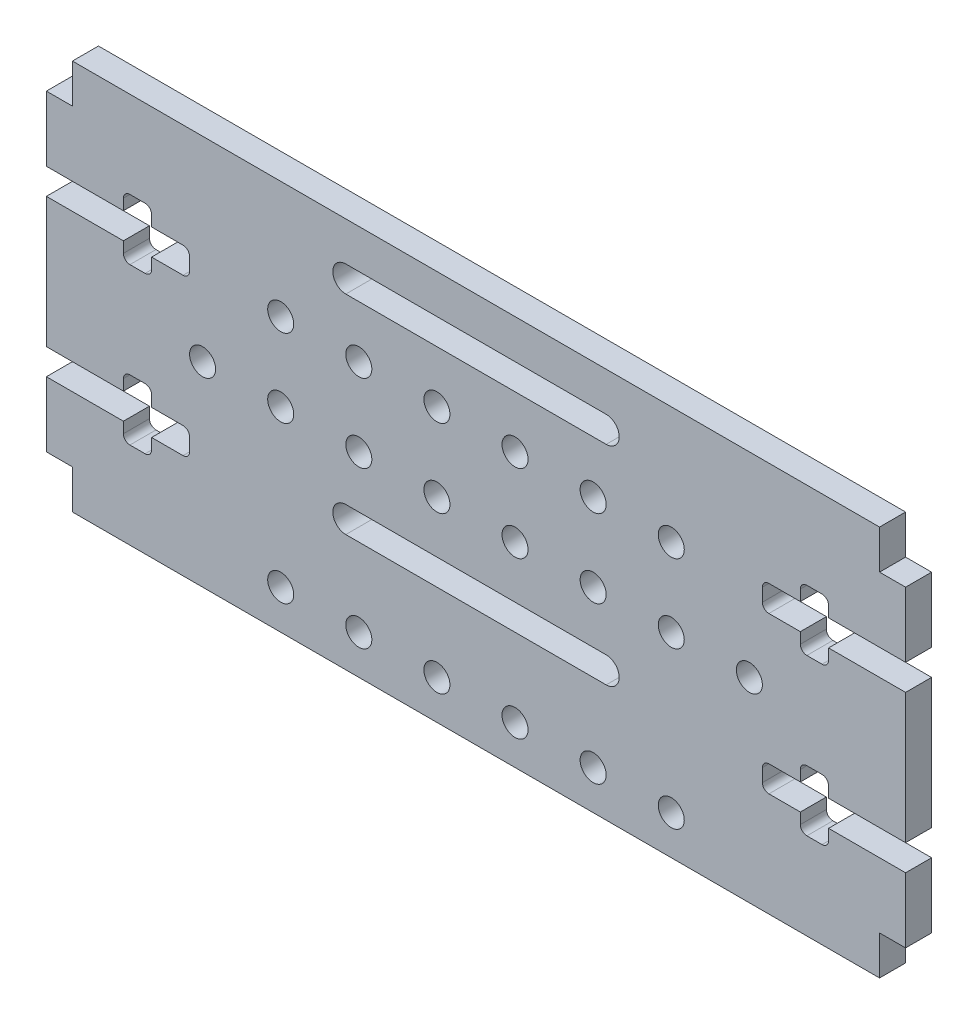
SolidWorks part; units mm, degrees
ref_plane "Alzado" through (0, 0, 0) normal (0, 0, 1) x (1, 0, 0)
ref_plane "Planta" through (0, 0, 0) normal (0, 1, 0) x (1, 0, 0)
ref_plane "Vista lateral" through (0, 0, 0) normal (1, 0, 0) x (0, 0, -1)
sketch "Model" plane through (0, 0, 0) normal (0, 0, 1) x (1, 0, 0)
  line L0 (-1383.7269, 374.4082) -> (-1386.7269, 374.4082)
  line L1 (-1383.7269, 338.4082) -> (-1386.7269, 338.4082)
  line L2 (-1386.7269, 378.9082) -> (-1479.7269, 378.9082)
  line L3 (-1479.7269, 333.9082) -> (-1386.7269, 333.9082)
  line L4 (-1479.7269, 374.4082) -> (-1482.7269, 374.4082)
  line L5 (-1479.7269, 338.4082) -> (-1482.7269, 338.4082)
  line L6 (-1383.7269, 348.9082) -> (-1383.7269, 363.9082)
  line L7 (-1482.7269, 348.9082) -> (-1482.7269, 363.9082)
  line L8 (-1482.7269, 366.9082) -> (-1482.7269, 374.4082)
  line L9 (-1482.7269, 338.4082) -> (-1482.7269, 345.9082)
  line L10 (-1383.7269, 338.4082) -> (-1383.7269, 345.9082)
  line L11 (-1383.7269, 366.9082) -> (-1383.7269, 374.4082)
  line L12 (-1448.2269, 350.4082) -> (-1418.2269, 350.4082)
  line L13 (-1448.2269, 347.4082) -> (-1418.2269, 347.4082)
  line L14 (-1448.2269, 374.4082) -> (-1418.2269, 374.4082)
  line L15 (-1448.2269, 371.4082) -> (-1418.2269, 371.4082)
  line L16 (-1479.7269, 374.4082) -> (-1479.7269, 378.9082)
  line L17 (-1386.7269, 378.9082) -> (-1386.7269, 374.4082)
  line L18 (-1386.7269, 338.4082) -> (-1386.7269, 333.9082)
  line L19 (-1479.7269, 333.9082) -> (-1479.7269, 338.4082)
  line L20 (-1383.7269, 345.9082) -> (-1392.6019, 345.9082)
  line L21 (-1392.6019, 348.9082) -> (-1383.7269, 348.9082)
  line L22 (-1399.4769, 348.9082) -> (-1395.8519, 348.9082)
  line L23 (-1395.8519, 345.9082) -> (-1399.4769, 345.9082)
  line L24 (-1400.2269, 346.6582) -> (-1400.2269, 348.1582)
  line L25 (-1473.8519, 345.9082) -> (-1482.7269, 345.9082)
  line L26 (-1482.7269, 348.9082) -> (-1473.8519, 348.9082)
  line L27 (-1466.9769, 345.9082) -> (-1470.6019, 345.9082)
  line L28 (-1470.6019, 348.9082) -> (-1466.9769, 348.9082)
  line L29 (-1466.2269, 348.1582) -> (-1466.2269, 346.6582)
  line L30 (-1473.1019, 350.9082) -> (-1471.3519, 350.9082)
  line L31 (-1471.3519, 343.9082) -> (-1473.1019, 343.9082)
  line L32 (-1473.8519, 348.9082) -> (-1473.8519, 350.1582)
  line L33 (-1470.6019, 348.9082) -> (-1470.6019, 350.1582)
  line L34 (-1473.8519, 345.9082) -> (-1473.8519, 344.6582)
  line L35 (-1470.6019, 345.9082) -> (-1470.6019, 344.6582)
  line L36 (-1395.1019, 350.9082) -> (-1393.3519, 350.9082)
  line L37 (-1393.3519, 343.9082) -> (-1395.1019, 343.9082)
  line L38 (-1395.8519, 348.9082) -> (-1395.8519, 350.1582)
  line L39 (-1392.6019, 348.9082) -> (-1392.6019, 350.1582)
  line L40 (-1395.8519, 345.9082) -> (-1395.8519, 344.6582)
  line L41 (-1392.6019, 345.9082) -> (-1392.6019, 344.6582)
  line L42 (-1473.8519, 363.9082) -> (-1482.7269, 363.9082)
  line L43 (-1482.7269, 366.9082) -> (-1473.8519, 366.9082)
  line L44 (-1466.9769, 363.9082) -> (-1470.6019, 363.9082)
  line L45 (-1470.6019, 366.9082) -> (-1466.9769, 366.9082)
  line L46 (-1466.2269, 366.1582) -> (-1466.2269, 364.6582)
  line L47 (-1473.1019, 368.9082) -> (-1471.3519, 368.9082)
  line L48 (-1471.3519, 361.9082) -> (-1473.1019, 361.9082)
  line L49 (-1473.8519, 366.9082) -> (-1473.8519, 368.1582)
  line L50 (-1470.6019, 366.9082) -> (-1470.6019, 368.1582)
  line L51 (-1473.8519, 363.9082) -> (-1473.8519, 362.6582)
  line L52 (-1470.6019, 363.9082) -> (-1470.6019, 362.6582)
  line L53 (-1383.7269, 363.9082) -> (-1392.6019, 363.9082)
  line L54 (-1392.6019, 366.9082) -> (-1383.7269, 366.9082)
  line L55 (-1399.4769, 366.9082) -> (-1395.8519, 366.9082)
  line L56 (-1395.8519, 363.9082) -> (-1399.4769, 363.9082)
  line L57 (-1400.2269, 364.6582) -> (-1400.2269, 366.1582)
  line L58 (-1395.1019, 368.9082) -> (-1393.3519, 368.9082)
  line L59 (-1393.3519, 361.9082) -> (-1395.1019, 361.9082)
  line L60 (-1395.8519, 366.9082) -> (-1395.8519, 368.1582)
  line L61 (-1392.6019, 366.9082) -> (-1392.6019, 368.1582)
  line L62 (-1395.8519, 363.9082) -> (-1395.8519, 362.6582)
  line L63 (-1392.6019, 363.9082) -> (-1392.6019, 362.6582)
  circle A0 centre (-1401.7275, 356.4082) radius 1.5
  circle A1 centre (-1464.7275, 356.4082) radius 1.5
  arc A2 (-1448.2269, 350.4082) -> (-1448.2269, 347.4082) centre (-1448.2269, 348.9082) ccw
  arc A3 (-1418.2269, 347.4082) -> (-1418.2269, 350.4082) centre (-1418.2269, 348.9082) ccw
  arc A4 (-1448.2269, 374.4082) -> (-1448.2269, 371.4082) centre (-1448.2269, 372.9082) ccw
  arc A5 (-1418.2269, 371.4082) -> (-1418.2269, 374.4082) centre (-1418.2269, 372.9082) ccw
  circle A6 centre (-1455.7275, 356.4082) radius 1.5
  circle A7 centre (-1410.7275, 356.4082) radius 1.5
  circle A8 centre (-1446.7275, 356.4082) radius 1.5
  circle A9 centre (-1437.7275, 356.4082) radius 1.5
  circle A10 centre (-1428.7275, 356.4082) radius 1.5
  circle A11 centre (-1419.7275, 356.4082) radius 1.5
  circle A12 centre (-1455.7275, 365.4082) radius 1.5
  circle A13 centre (-1446.7275, 365.4082) radius 1.5
  circle A14 centre (-1437.7275, 365.4082) radius 1.5
  circle A15 centre (-1428.7275, 365.4082) radius 1.5
  circle A16 centre (-1419.7275, 365.4082) radius 1.5
  circle A17 centre (-1410.7275, 365.4082) radius 1.5
  circle A18 centre (-1455.7275, 338.4082) radius 1.5
  circle A19 centre (-1446.7275, 338.4082) radius 1.5
  circle A20 centre (-1437.7275, 338.4082) radius 1.5
  circle A21 centre (-1428.7275, 338.4082) radius 1.5
  circle A22 centre (-1419.7275, 338.4082) radius 1.5
  circle A23 centre (-1410.7275, 338.4082) radius 1.5
  arc A24 (-1473.1019, 350.9082) -> (-1473.8519, 350.1582) centre (-1473.1019, 350.1582) ccw
  arc A25 (-1470.6019, 350.1582) -> (-1471.3519, 350.9082) centre (-1471.3519, 350.1582) ccw
  arc A26 (-1471.3519, 343.9082) -> (-1470.6019, 344.6582) centre (-1471.3519, 344.6582) ccw
  arc A27 (-1473.8519, 344.6582) -> (-1473.1019, 343.9082) centre (-1473.1019, 344.6582) ccw
  arc A28 (-1466.2269, 348.1582) -> (-1466.9769, 348.9082) centre (-1466.9769, 348.1582) ccw
  arc A29 (-1466.9769, 345.9082) -> (-1466.2269, 346.6582) centre (-1466.9769, 346.6582) ccw
  arc A30 (-1399.4769, 348.9082) -> (-1400.2269, 348.1582) centre (-1399.4769, 348.1582) ccw
  arc A31 (-1400.2269, 346.6582) -> (-1399.4769, 345.9082) centre (-1399.4769, 346.6582) ccw
  arc A32 (-1395.1019, 350.9082) -> (-1395.8519, 350.1582) centre (-1395.1019, 350.1582) ccw
  arc A33 (-1392.6019, 350.1582) -> (-1393.3519, 350.9082) centre (-1393.3519, 350.1582) ccw
  arc A34 (-1393.3519, 343.9082) -> (-1392.6019, 344.6582) centre (-1393.3519, 344.6582) ccw
  arc A35 (-1395.8519, 344.6582) -> (-1395.1019, 343.9082) centre (-1395.1019, 344.6582) ccw
  arc A36 (-1473.1019, 368.9082) -> (-1473.8519, 368.1582) centre (-1473.1019, 368.1582) ccw
  arc A37 (-1470.6019, 368.1582) -> (-1471.3519, 368.9082) centre (-1471.3519, 368.1582) ccw
  arc A38 (-1471.3519, 361.9082) -> (-1470.6019, 362.6582) centre (-1471.3519, 362.6582) ccw
  arc A39 (-1473.8519, 362.6582) -> (-1473.1019, 361.9082) centre (-1473.1019, 362.6582) ccw
  arc A40 (-1466.2269, 366.1582) -> (-1466.9769, 366.9082) centre (-1466.9769, 366.1582) ccw
  arc A41 (-1466.9769, 363.9082) -> (-1466.2269, 364.6582) centre (-1466.9769, 364.6582) ccw
  arc A42 (-1399.4769, 366.9082) -> (-1400.2269, 366.1582) centre (-1399.4769, 366.1582) ccw
  arc A43 (-1400.2269, 364.6582) -> (-1399.4769, 363.9082) centre (-1399.4769, 364.6582) ccw
  arc A44 (-1395.1019, 368.9082) -> (-1395.8519, 368.1582) centre (-1395.1019, 368.1582) ccw
  arc A45 (-1392.6019, 368.1582) -> (-1393.3519, 368.9082) centre (-1393.3519, 368.1582) ccw
  arc A46 (-1393.3519, 361.9082) -> (-1392.6019, 362.6582) centre (-1393.3519, 362.6582) ccw
  arc A47 (-1395.8519, 362.6582) -> (-1395.1019, 361.9082) centre (-1395.1019, 362.6582) ccw
extrude "Saliente-Extruir1" add sketch "Model" along normal blind 3
